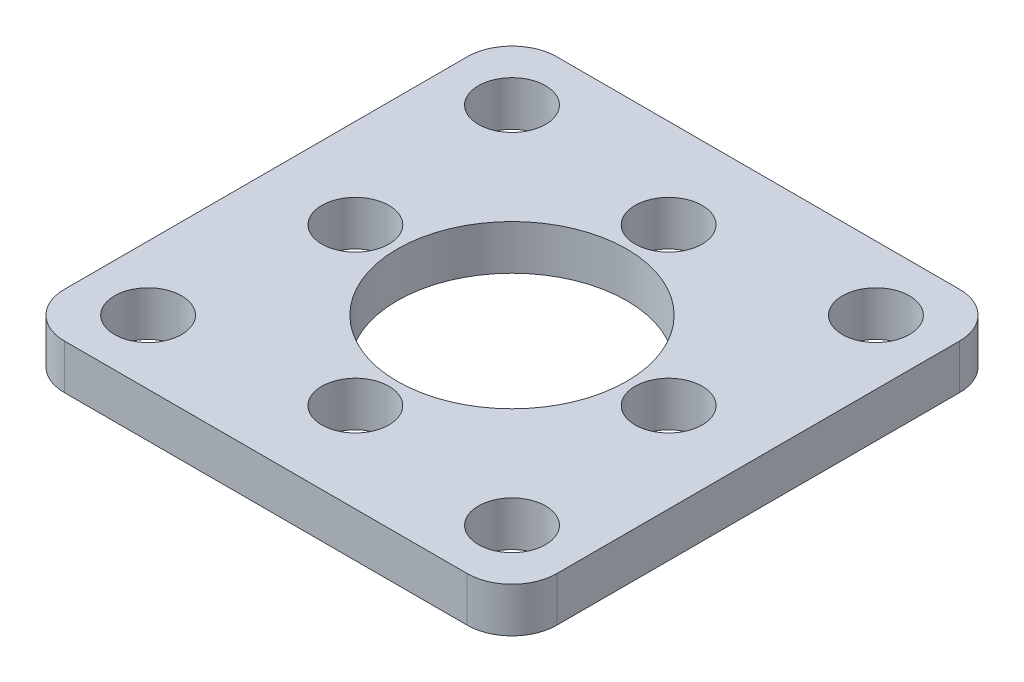
SolidWorks part; units mm, degrees
material "Thornel Mat VMA"
ref_plane "前视基准面" through (0, 0, 0) normal (0, 0, 1) x (1, 0, 0)
ref_plane "上视基准面" through (0, 0, 0) normal (0, 1, 0) x (1, 0, 0)
ref_plane "右视基准面" through (0, 0, 0) normal (1, 0, 0) x (0, 0, -1)
sketch "草图1" plane through (0, 0, 0) normal (0, 1, 0) x (1, 0, 0)
  line L0 (-11.0012, 11.0012) -> (11.0012, -11.0012) construction
  line L1 (-11.0012, 11.0012) -> (11.0012, 11.0012)
  line L2 (-11.0012, 11.0012) -> (-11.0012, -11.0012)
  line L3 (-11.0012, -11.0012) -> (11.0012, -11.0012)
  line L4 (11.0012, 11.0012) -> (11.0012, -11.0012)
  line L5 (0, -11.0012) -> (0, 11.0012) construction
  line L6 (-11.0012, 0) -> (11.0012, 0) construction
  line L7 (11.0012, 11.0012) -> (-11.0012, -11.0012) construction
  circle A0 centre (-8.1317, 8.1317) radius 1.5
  circle A1 centre (8.1317, -8.1317) radius 1.5
  circle A2 centre (8.1317, 8.1317) radius 1.5
  circle A3 centre (-8.1317, -8.1317) radius 1.5
  point P0 (0, 0)
  dimension "D2" = 3
  dimension "D3" = 23
  dimension "D1" = 45
extrude "凸台-拉伸1" add sketch "草图1" along normal blind 2
fillet "圆角1" radius 2 4 edges at (-11.0012, 1, -11.0012) (11.0012, 1, -11.0012) (11.0012, 1, 11.0012) (-11.0012, 1, 11.0012)
sketch "草图3" plane through (0, 0, 0) normal (0, 1, 0) x (1, 0, 0)
  line L0 (-11.0012, 0) -> (11.0012, 0) construction
  line L1 (-11.0012, 9.0012) -> (-11.0012, -9.0012) construction
  line L2 (11.0012, -9.0012) -> (11.0012, 9.0012) construction
  line L3 (0, 11.0012) -> (0, -11.0012) construction
  line L4 (9.0012, 11.0012) -> (-9.0012, 11.0012) construction
  line L5 (-9.0012, -11.0012) -> (9.0012, -11.0012) construction
  line L6 (-8.1317, 8.1317) -> (8.1317, -8.1317) construction
  line L7 (8.1317, 8.1317) -> (-8.1317, -8.1317) construction
  circle A0 centre (-7, 0) radius 1.5
  circle A1 centre (7, 0) radius 1.5
  circle A2 centre (0, 7) radius 1.5
  circle A3 centre (0, -7) radius 1.5
  dimension "D1" = 3
  dimension "D2" = 14
extrude "切除-拉伸2" cut sketch "草图3" along normal blind 10
sketch "草图4" plane through (0, 0, 0) normal (0, -1, 0) x (1, 0, 0)
  circle A0 centre (0, 0) radius 5.125
  dimension "D1" = 10.25
extrude "切除-拉伸3" cut sketch "草图4" against normal blind 10
